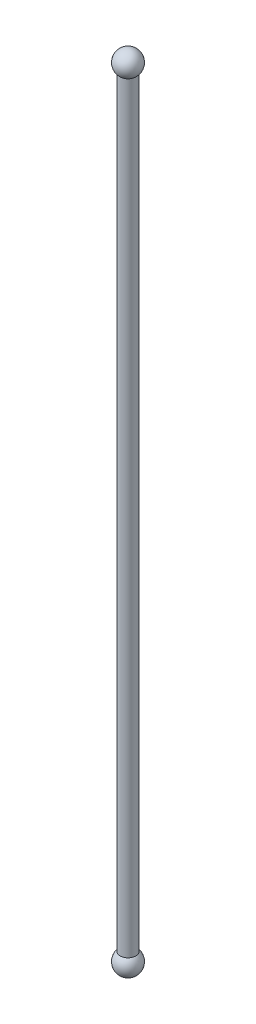
SolidWorks part; units mm, degrees
ref_plane "前视基准面" through (0, 0, 0) normal (0, 0, 1) x (1, 0, 0)
ref_plane "上视基准面" through (0, 0, 0) normal (0, 1, 0) x (1, 0, 0)
ref_plane "右视基准面" through (0, 0, 0) normal (1, 0, 0) x (0, 0, -1)
sketch "草图2" plane through (0, 0, 0) normal (0, 1, 0) x (1, 0, 0)
  circle A0 centre (0, 0) radius 5
  dimension "D1" = 10
extrude "凸台-拉伸1" add sketch "草图2" along normal mid plane 500
sketch "草图3" plane through (0, 0, 0) normal (0, 0, 1) x (1, 0, 0)
  line L0 (5, 250) -> (-5, 250) construction
  line L1 (0, 257.5) -> (0, 242.5)
  arc A0 (0, 242.5) -> (0, 257.5) centre (0, 250) ccw
  dimension "D1" = 15
revolve "旋转1" add sketch "草图3" angle 360 about L1
mirror "镜向1" about plane through (0, 0, 0) normal (0, 1, 0) of "旋转1"
